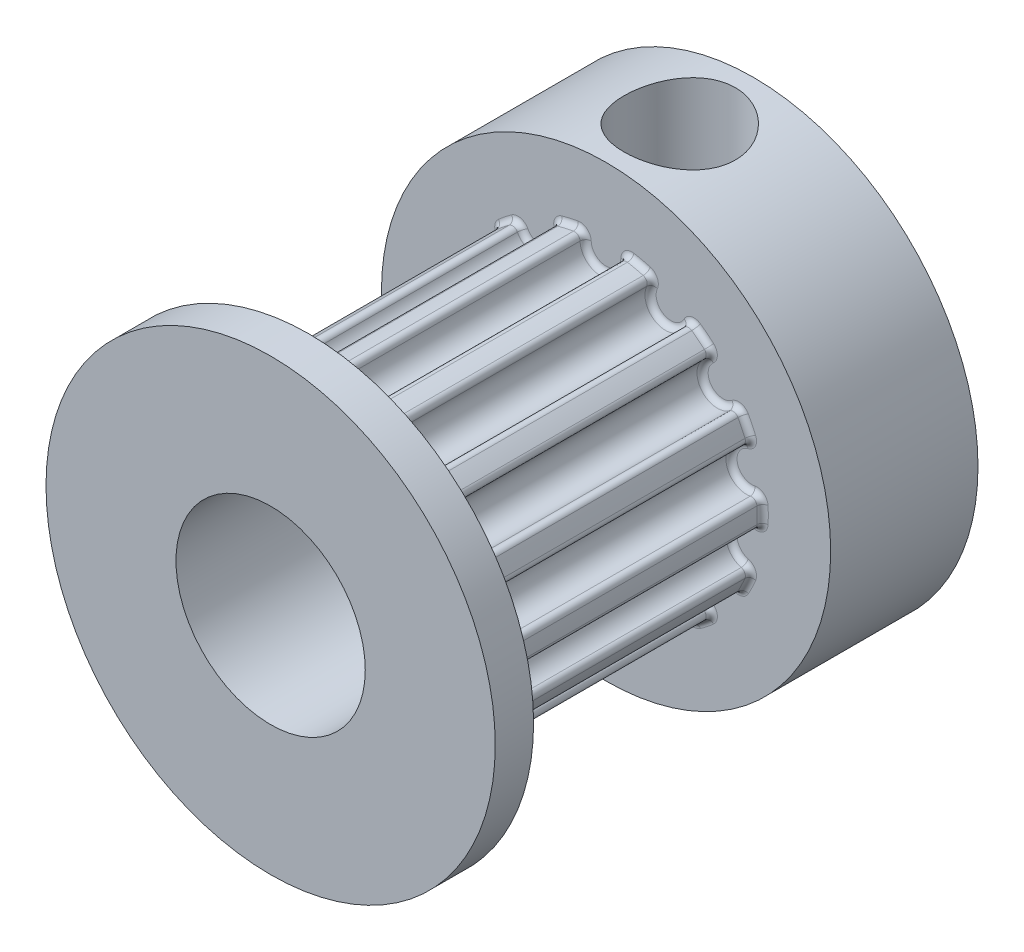
SolidWorks part; units mm, degrees
ref_plane "Front Plane" through (0, 0, 0) normal (0, 0, 1) x (1, 0, 0)
ref_plane "Top Plane" through (0, 0, 0) normal (0, 1, 0) x (1, 0, 0)
ref_plane "Right Plane" through (0, 0, 0) normal (1, 0, 0) x (0, 0, -1)
sketch "Sketch1" plane through (0, 0, 0) normal (1, 0, 0) x (0, 0, -1)
  line L0 (0, 0) -> (57.5696, 0) construction
  line L2 (0, 6.0488) -> (1.0323, 6.0488)
  line L3 (13, 2.5488) -> (13, 6.0488)
  line L4 (1.0323, 6.0488) -> (1.0323, 4.2193)
  line L5 (1.0323, 4.2193) -> (9.0323, 4.2193)
  line L6 (9.0323, 6.0488) -> (9.0323, 4.2193)
  line L7 (0, 6.0488) -> (0, 2.5488)
  line L8 (0, 2.5488) -> (13, 2.5488)
  line L9 (13, 6.0488) -> (9.0323, 6.0488)
  point P12 (0, 0)
revolve "Revolve1" add sketch "Sketch1" angle 360 about L0
sketch "Sketch2" plane through (0, 0, -9.0323) normal (0, 0, 1) x (1, 0, 0)
  arc A0 (-2.9443, 3.0222) -> (-3.6016, 2.198) centre (0, 0) ccw
  arc A1 (-0.5271, 4.1863) -> (0.5271, 4.1863) centre (0, 4.0293) ccw
  arc A2 (1.3414, 4.0004) -> (2.2913, 3.543) centre (1.7483, 3.6303) ccw
  arc A3 (2.9443, 3.0222) -> (3.6016, 2.198) centre (3.1503, 2.5122) ccw
  arc A4 (3.964, 1.4455) -> (4.1986, 0.4176) centre (3.9283, 0.8966) ccw
  arc A5 (4.1986, -0.4176) -> (3.964, -1.4455) centre (3.9283, -0.8966) ccw
  arc A6 (3.6016, -2.198) -> (2.9443, -3.0222) centre (3.1503, -2.5122) ccw
  arc A7 (2.2913, -3.543) -> (1.3414, -4.0004) centre (1.7483, -3.6303) ccw
  arc A8 (0.5271, -4.1863) -> (-0.5271, -4.1863) centre (0, -4.0293) ccw
  arc A9 (-1.3414, -4.0004) -> (-2.2913, -3.543) centre (-1.7483, -3.6303) ccw
  arc A10 (-2.9443, -3.0222) -> (-3.6016, -2.198) centre (-3.1503, -2.5122) ccw
  arc A11 (-3.964, -1.4455) -> (-4.1986, -0.4176) centre (-3.9283, -0.8966) ccw
  arc A12 (-4.1986, 0.4176) -> (-3.964, 1.4455) centre (-3.9283, 0.8966) ccw
  arc A13 (-3.6016, 2.198) -> (-2.9443, 3.0222) centre (-3.1503, 2.5122) ccw
  arc A14 (-2.2913, 3.543) -> (-1.3414, 4.0004) centre (-1.7483, 3.6303) ccw
  arc A15 (-1.3414, 4.0004) -> (-2.2913, 3.543) centre (0, 0) ccw
  arc A16 (0.5271, 4.1863) -> (-0.5271, 4.1863) centre (0, 0) ccw
  arc A17 (2.2913, 3.543) -> (1.3414, 4.0004) centre (0, 0) ccw
  arc A18 (3.6016, 2.198) -> (2.9443, 3.0222) centre (0, 0) ccw
  arc A19 (4.1986, 0.4176) -> (3.964, 1.4455) centre (0, 0) ccw
  arc A20 (3.964, -1.4455) -> (4.1986, -0.4176) centre (0, 0) ccw
  arc A21 (2.9443, -3.0222) -> (3.6016, -2.198) centre (0, 0) ccw
  arc A22 (1.3414, -4.0004) -> (2.2913, -3.543) centre (0, 0) ccw
  arc A23 (-0.5271, -4.1863) -> (0.5271, -4.1863) centre (0, 0) ccw
  arc A24 (-2.2913, -3.543) -> (-1.3414, -4.0004) centre (0, 0) ccw
  arc A25 (-3.6016, -2.198) -> (-2.9443, -3.0222) centre (0, 0) ccw
  arc A26 (-4.1986, -0.4176) -> (-3.964, -1.4455) centre (0, 0) ccw
  arc A27 (-3.964, 1.4455) -> (-4.1986, 0.4176) centre (0, 0) ccw
  point P48 (0, 0)
  dimension "D1" = 14
extrude "Cut-Extrude2" cut sketch "Sketch2" along normal up to surface (8 mm away) up to face at (6.0488, 0, -1.0323)
fillet "Fillet1" radius 0.15 84 edges at (3.3921, -0.7742, -1.0323) (3.3921, -0.7742, -9.0323) (2.7203, -2.1693, -1.0323) (2.7203, -2.1693, -9.0323) (1.5096, -3.1348, -1.0323) (1.5096, -3.1348, -9.0323) (0, -3.4793, -1.0323) (0, -3.4793, -9.0323) (-1.5096, -3.1348, -1.0323) (-1.5096, -3.1348, -9.0323) (-2.7203, -2.1693, -1.0323) (-2.7203, -2.1693, -9.0323) (-3.3921, -0.7742, -1.0323) (-3.3921, -0.7742, -9.0323) (-3.3921, 0.7742, -1.0323) (-3.3921, 0.7742, -9.0323) (-2.7203, 2.1693, -1.0323) (-2.7203, 2.1693, -9.0323) (-1.5096, 3.1348, -1.0323) (-1.5096, 3.1348, -9.0323) (0, 3.4793, -1.0323) (0, 3.4793, -9.0323) (1.5096, 3.1348, -1.0323) (1.5096, 3.1348, -9.0323) (3.3921, 0.7742, -1.0323) (3.3921, 0.7742, -9.0323) (2.7203, 2.1693, -1.0323) (2.7203, 2.1693, -9.0323) (4.2193, 0, -9.0323) (3.964, -1.4455, -5.0323) (4.1986, -0.4176, -5.0323) (4.2193, 0, -1.0323) (4.1986, 0.4176, -5.0323) (3.964, 1.4455, -5.0323) (3.8015, -1.8307, -9.0323) (2.9443, -3.0222, -5.0323) (3.6016, -2.198, -5.0323) (3.8015, -1.8307, -1.0323) (2.6307, -3.2988, -9.0323) (1.3414, -4.0004, -5.0323) (2.2913, -3.543, -5.0323) (2.6307, -3.2988, -1.0323) (0.9389, -4.1135, -9.0323) (-0.5271, -4.1863, -5.0323) (0.5271, -4.1863, -5.0323) (0.9389, -4.1135, -1.0323) (-0.9389, -4.1135, -9.0323) (-2.2913, -3.543, -5.0323) (-1.3414, -4.0004, -5.0323) (-0.9389, -4.1135, -1.0323) (-2.6307, -3.2988, -9.0323) (-3.6016, -2.198, -5.0323) (-2.9443, -3.0222, -5.0323) (-2.6307, -3.2988, -1.0323) (-3.8015, -1.8307, -9.0323) (-4.1986, -0.4176, -5.0323) (-3.964, -1.4455, -5.0323) (-3.8015, -1.8307, -1.0323) (-4.2193, 0, -9.0323) (-3.964, 1.4455, -5.0323) (-4.1986, 0.4176, -5.0323) (-4.2193, 0, -1.0323) (-3.8015, 1.8307, -9.0323) (-2.9443, 3.0222, -5.0323) (-3.6016, 2.198, -5.0323) (-3.8015, 1.8307, -1.0323) (-2.6307, 3.2988, -9.0323) (-1.3414, 4.0004, -5.0323) (-2.2913, 3.543, -5.0323) (-2.6307, 3.2988, -1.0323) (-0.9389, 4.1135, -9.0323) (0.5271, 4.1863, -5.0323) (-0.5271, 4.1863, -5.0323) (-0.9389, 4.1135, -1.0323) (0.9389, 4.1135, -1.0323) (0.9389, 4.1135, -9.0323) (2.2913, 3.543, -5.0323) (1.3414, 4.0004, -5.0323) (2.6307, 3.2988, -9.0323) (3.6016, 2.198, -5.0323) (2.9443, 3.0222, -5.0323) (2.6307, 3.2988, -1.0323) (3.8015, 1.8307, -9.0323) (3.8015, 1.8307, -1.0323)
sketch "Sketch3" plane through (0, 0, 0) normal (0, 1, 0) x (1, 0, 0)
  circle A0 centre (0, 11.0162) radius 1.5
extrude "Cut-Extrude3" cut sketch "Sketch3" along normal blind 10 contours A0
